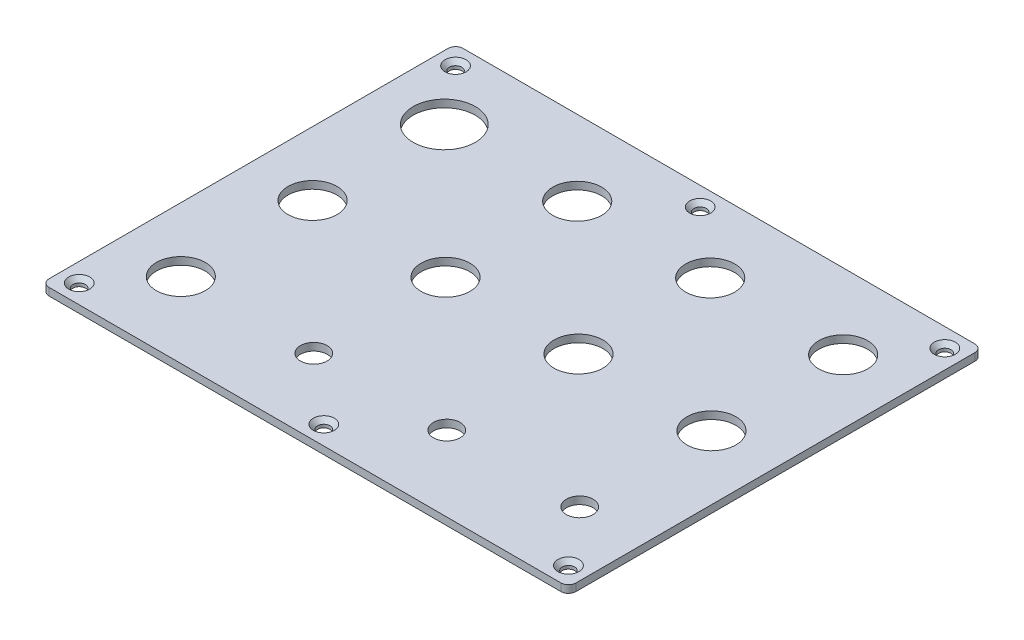
SolidWorks part; units mm, degrees
ref_plane "Front Plane" through (0, 0, 0) normal (0, 0, 1) x (1, 0, 0)
ref_plane "Top Plane" through (0, 0, 0) normal (0, 1, 0) x (1, 0, 0)
ref_plane "Right Plane" through (0, 0, 0) normal (1, 0, 0) x (0, 0, -1)
sketch "Bottom Plate" plane through (0, 0, 0) normal (0, 1, 0) x (1, 0, 0)
  line L1 (0, 0) -> (-140, 0)
  line L2 (0, 0) -> (0, 110)
  line L3 (0, 110) -> (-140, 110)
  line L4 (-140, 0) -> (-140, 110)
  dimension "D1" = 140
  dimension "D2" = 110
extrude "Bottom Plate EXT" add sketch "Bottom Plate" along normal blind 2
sketch "Top Row" plane through (0, 2, 0) normal (0, 1, 0) x (1, 0, 0)
  line L0 (0, 0) -> (0, 110) construction
  line L1 (-140, 110) -> (-140, 0) construction
  line L2 (-123, 90) -> (-17, 90) construction
  line L3 (0, 110) -> (-140, 110) construction
  line L7 (-58.8333, 90) -> (-17, 90) construction
  circle A0 centre (-123, 90) radius 8.25
  circle A1 centre (-87.6667, 90) radius 6.5
  circle A2 centre (-52.3333, 90) radius 6.5
  circle A3 centre (-17, 90) radius 6.5
  dimension "D1" = 16.5
  dimension "D2" = 20
  dimension "D7" = 13
  dimension "D8" = 35.3333
  dimension "D9" = 13
  dimension "D3" = 17
  dimension "D4" = 35.3333
  dimension "D5" = 106
  dimension "D6" = 17
extrude "Top Row Cut" cut sketch "Top Row" against normal through all
sketch "Sketch2" plane through (0, 2, 0) normal (0, 1, 0) x (1, 0, 0)
  line L0 (-140, 20) -> (0, 20) construction
  line L1 (-140, 110) -> (-140, 0) construction
  line L2 (0, 0) -> (0, 110) construction
  line L3 (-140, 0) -> (0, 0) construction
  circle A0 centre (-123, 20) radius 6.5
  circle A1 centre (-87.6667, 20) radius 3.55
  circle A2 centre (-52.3333, 20) radius 3.55
  circle A3 centre (-17, 20) radius 3.55
  dimension "D1" = 13
  dimension "D7" = 7.1
  dimension "D2" = 20
  dimension "D3" = 35.3333
  dimension "D4" = 35.3333
  dimension "D5" = 35.3333
  dimension "D6" = 17
extrude "Bottom Row Cut" cut sketch "Sketch2" against normal blind 10
sketch "Sketch3" plane through (0, 2, 0) normal (0, 1, 0) x (1, 0, 0)
  line L0 (-123, 55) -> (-4.6477, 55) construction
  line L1 (-123, 90) -> (-123, 20) construction
  circle A0 centre (-123, 55) radius 6.5
  circle A1 centre (-87.6667, 55) radius 6.5
  circle A2 centre (-52.3333, 55) radius 6.5
  circle A3 centre (-17, 55) radius 6.5
  dimension "D1" = 13
  dimension "D2" = 35.3333
  dimension "D3" = 35.3333
  dimension "D4" = 35.3333
extrude "Center Row Cut" cut sketch "Sketch3" against normal blind 10
sketch "Plate Screws" plane through (0, 2, 0) normal (0, 1, 0) x (1, 0, 0)
  line L0 (0, 110) -> (-140, 110) construction
  line L1 (-140, 110) -> (-140, 0) construction
  line L2 (-140, 0) -> (0, 0) construction
  line L3 (0, 0) -> (0, 110) construction
  line L4 (-70, 110) -> (-70, 59.8221) construction
  line L5 (0, 55) -> (-30.2044, 55) construction
  circle A0 centre (-135, 105) radius 1.65
  circle A1 centre (-5, 105) radius 1.65
  circle A2 centre (-5, 5) radius 1.65
  circle A3 centre (-135, 5) radius 1.65
  circle A4 centre (-70, 105) radius 1.65
  circle A5 centre (-70, 5) radius 1.65
  dimension "D1" = 3.3
  dimension "D2" = 5
  dimension "D3" = 5
  dimension "D4" = 5
  dimension "D5" = 5
extrude "Plate Screws Cut" cut sketch "Plate Screws" against normal through all
sketch "Plate Screw Head" plane through (0, 2, 0) normal (0, 1, 0) x (1, 0, 0)
  line L0 (-70, 110) -> (-70, 73.7034) construction
  line L1 (0, 110) -> (-140, 110) construction
  line L2 (0, 55) -> (-52.6177, 55) construction
  line L3 (0, 0) -> (0, 110) construction
  circle A0 centre (-135, 105) radius 2.8
  circle A1 centre (-5, 105) radius 2.8
  circle A2 centre (-5, 5) radius 2.8
  circle A3 centre (-135, 5) radius 2.8
  circle A4 centre (-70, 105) radius 2.8
  circle A5 centre (-70, 5) radius 2.8
  dimension "D1" = 5.6
extrude "Plate Screw Head Cut" cut sketch "Plate Screw Head" against normal blind 2 draft 45
fillet "Fillet1" radius 2 1 edges at (-140, 1, -110)
fillet "Fillet2" radius 2 1 edges at (0, 1, -110)
fillet "Fillet3" radius 2 1 edges at (0, 1, 0)
fillet "Fillet4" radius 2 1 edges at (-140, 1, 0)
equation "\"SPACER_THIRD\"= \"D5@Top Row\" / 3mm"
equation "\"SPACER_SIDE\"= 17mm"
equation "\"SPACER_TOP\"= 20mm"
equation "\"BUTTON_METAL\"=16.5"
equation "\"BUTTON_PUSH\"=13"
equation "\"SPACER_BOTTOM\"= 20mm"
equation "\"D1@Sketch2\"=\"BUTTON_PUSH\""
equation "\"D2@Sketch2\"=\"SPACER_BOTTOM\""
equation "\"D3@Sketch2\"=\"SPACER_THIRD\""
equation "\"D4@Sketch2\"=\"SPACER_THIRD\""
equation "\"D5@Sketch2\"=\"SPACER_THIRD\""
equation "\"D6@Sketch2\"=\"SPACER_SIDE\""
equation "\"D1@Sketch3\"=\"BUTTON_PUSH\""
equation "\"D2@Sketch3\"=\"SPACER_THIRD\""
equation "\"D3@Sketch3\"=\"SPACER_THIRD\""
equation "\"D4@Sketch3\"=\"SPACER_THIRD\""
equation "\"D9@Top Row\"=\"BUTTON_PUSH\""
equation "\"D7@Top Row\"=\"BUTTON_PUSH\""
equation "\"D1@Top Row\"=\"BUTTON_METAL\""
equation "\"D2@Top Row\"=\"SPACER_TOP\""
equation "\"D4@Top Row\"=\"SPACER_THIRD\""
equation "\"D8@Top Row\"=\"SPACER_THIRD\""
equation "\"D6@Top Row\"=\"SPACER_SIDE\""
equation "\"D3@Top Row\"=\"SPACER_SIDE\""
equation "\"ROTARY_ENCODERS\"=7.1"
equation "\"D7@Sketch2\"=\"ROTARY_ENCODERS\""
